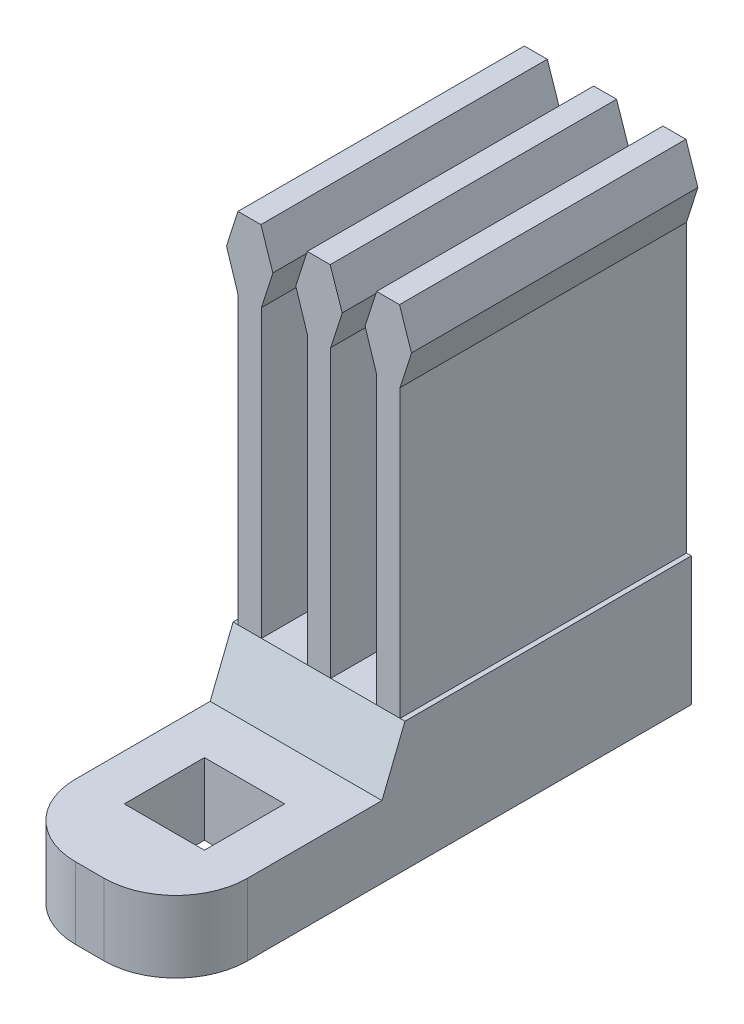
SolidWorks part; units mm, degrees
ref_plane "Plano frontal" through (0, 0, 0) normal (0, 0, 1) x (1, 0, 0)
ref_plane "Plano superior" through (0, 0, 0) normal (0, 1, 0) x (1, 0, 0)
ref_plane "Plano direito" through (0, 0, 0) normal (1, 0, 0) x (0, 0, -1)
sketch "Esboço1" plane through (0, 0, 0) normal (0, 0, 1) x (1, 0, 0)
  line L0 (-0.4, 0) -> (-0.57, 0)
  line L1 (0, 0) -> (0, 10) construction
  line L2 (0, 10) -> (0.42, 10) construction
  line L3 (0, 10) -> (-0.4, 10) construction
  line L4 (-0.4, 10) -> (-0.4, 0)
  line L5 (0.42, 10) -> (0.42, 0)
  line L6 (0.42, 0) -> (2.02, 0)
  line L7 (2.02, 10) -> (2.02, 0)
  line L8 (-0.57, -2.5) -> (5.43, -2.5)
  line L9 (0.42, 10) -> (0.82, 11.25)
  line L10 (-0.4, 12.5) -> (0.4, 12.5)
  line L11 (0.4, 12.5) -> (0.82, 11.25)
  line L12 (-0.4, 10) -> (-0.8, 11.25)
  line L13 (-0.4, 12.5) -> (-0.8, 11.25)
  line L14 (2.84, 10) -> (2.84, 0)
  line L15 (2.84, 0) -> (4.44, 0)
  line L16 (2.84, 10) -> (3.24, 11.25)
  line L17 (2.02, 12.5) -> (2.82, 12.5)
  line L18 (2.82, 12.5) -> (3.24, 11.25)
  line L19 (2.02, 10) -> (1.62, 11.25)
  line L20 (2.02, 12.5) -> (1.62, 11.25)
  line L21 (2.43, 0) -> (2.43, 10) construction
  line L22 (2.43, 10) -> (2.84, 10) construction
  line L23 (2.43, 10) -> (2.02, 10) construction
  line L24 (5.43, -2.5) -> (5.43, 0)
  line L25 (-0.57, -2.5) -> (-0.57, 0)
  line L34 (4.44, 10) -> (4.44, 0)
  line L35 (5.26, 10) -> (5.26, 0)
  line L36 (5.26, 0) -> (5.43, 0)
  line L37 (5.26, 10) -> (5.66, 11.25)
  line L38 (4.44, 12.5) -> (5.24, 12.5)
  line L39 (5.24, 12.5) -> (5.66, 11.25)
  line L42 (4.44, 10) -> (4.04, 11.25)
  line L43 (4.44, 12.5) -> (4.04, 11.25)
  line L44 (4.84, 0) -> (4.84, 10) construction
  line L45 (4.84, 10) -> (5.26, 10) construction
  line L46 (4.84, 10) -> (4.44, 10) construction
  point P4 (2, 12)
  point P32 (2.43, -2.5)
  dimension "D4" = 3
  dimension "D1" = 10
  dimension "D5" = 0.82
  dimension "D6" = 0.82
  dimension "D7" = 1.6
  dimension "D8" = 1.6
  dimension "D9" = 0.82
extrude "Ressalto-extrusão1" add sketch "Esboço1" along normal blind 10 contours L12 L13 L10 L11 L9 L5 L6 L7 L19 L20 L17 L18 L16 L14 L15 L34 L42 L43 L38 L39 L37 L35 L36 L24 L8 L25 L0 L4
sketch "Esboço2" plane through (0, 0, 10) normal (0, 0, 1) x (1, 0, 0)
  line L1 (-0.57, -2.5) -> (5.43, -2.5)
  line L2 (-0.57, -2.5) -> (-0.57, 0)
  line L3 (-0.57, 0) -> (5.43, 0)
  line L4 (5.43, -2.5) -> (5.43, 0)
extrude "Ressalto-extrusão2" add sketch "Esboço2" along normal blind 8
sketch "Esboço3" plane through (0, -2.5, 0) normal (0, -1, 0) x (1, 0, 0)
  line L0 (2.43, 18) -> (2.43, 14) construction
  line L1 (-0.57, 18) -> (5.43, 18) construction
  line L3 (1.03, 15.4) -> (3.83, 15.4)
  line L4 (1.03, 15.4) -> (1.03, 12.6)
  line L5 (1.03, 12.6) -> (3.83, 12.6)
  line L6 (3.83, 15.4) -> (3.83, 12.6)
  line L7 (1.03, 15.4) -> (3.83, 12.6) construction
  line L8 (1.03, 12.6) -> (3.83, 15.4) construction
  dimension "D1" = 2.8
extrude "Corte-extrusão1" cut sketch "Esboço3" against normal through all
sketch "Esboço4" plane through (0, -2.5, 0) normal (0, -1, 0) x (1, 0, 0)
  line L0 (3.83, 12.6) -> (3.83, 15.4) construction
  line L1 (1.03, 12.6) -> (3.83, 12.6) construction
  line L2 (1.03, 15.4) -> (1.03, 12.6) construction
  line L3 (3.83, 15.4) -> (1.03, 15.4) construction
  line L4 (-0.57, 0) -> (5.43, 0)
  line L5 (5.43, 0) -> (5.43, 18)
  line L6 (5.43, 18) -> (-0.57, 18)
  line L7 (-0.57, 18) -> (-0.57, 0)
  line L8 (-0.57, 0) -> (5.43, 0)
  line L9 (5.43, 0) -> (5.43, 18)
  line L10 (5.43, 18) -> (-0.57, 18)
  line L11 (-0.57, 18) -> (-0.57, 0)
  line L12 (3.83, 12.6) -> (3.83, 15.4)
  line L13 (1.03, 12.6) -> (3.83, 12.6)
  line L14 (1.03, 15.4) -> (1.03, 12.6)
  line L15 (3.83, 15.4) -> (1.03, 15.4)
  dimension "D1" = 0
extrude "Ressalto-extrusão3" add sketch "Esboço4" along normal blind 2
sketch "Esboço6" plane through (0, 0, 0) normal (1, 0, 0) x (0, 0, -1)
  line L0 (-18, 0) -> (-18, -2)
  line L1 (-18, -4.5) -> (-18, 0) construction
  line L2 (-18, -2) -> (-14, -2) construction
  line L3 (-14, -2) -> (-10.8, -2)
  line L4 (-10.8, -2) -> (-10, 0)
  line L5 (-10, 0) -> (-18, 0)
  line L6 (-18, -2) -> (-14, -2)
  dimension "D1" = 2
extrude "Corte-extrusão3" cut sketch "Esboço6" against normal through all and the other way through all
sketch "Esboço7" plane through (0, -2, 0) normal (0, 1, 0) x (1, 0, 0)
  line L0 (-0.57, -15.5) -> (-3.3213, -15.5)
  line L1 (-3.3213, -15.5) -> (-3.3213, -18.8576)
  line L2 (-3.3213, -18.8576) -> (8.5469, -18.8576)
  line L3 (8.5469, -18.8576) -> (8.5469, -15.5)
  line L4 (-0.57, -10.8) -> (-0.57, -18)
  line L5 (-0.57, -18) -> (5.43, -18)
  line L6 (5.43, -18) -> (5.43, -10.8)
  line L7 (5.43, -10.8) -> (-0.57, -10.8)
  line L9 (1.93, -18) -> (2.93, -18)
  line L12 (8.5469, -15.5) -> (5.43, -15.5)
  arc A0 (2.93, -18) -> (5.43, -15.5) centre (2.93, -15.5) ccw
  arc A1 (-0.57, -15.5) -> (1.93, -18) centre (1.93, -15.5) ccw
  dimension "D2" = 2.5
  dimension "D1" = 0
extrude "Corte-extrusão4" cut sketch "Esboço7" against normal through all
